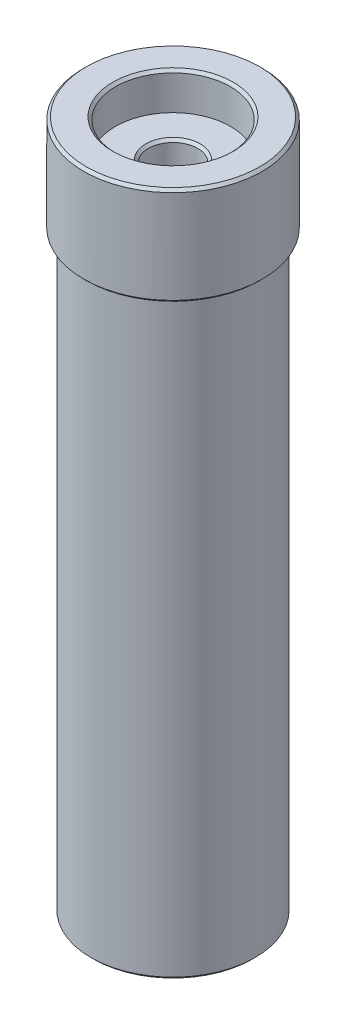
SolidWorks part; units mm, degrees
ref_plane "Front Plane" through (0, 0, 0) normal (0, 0, 1) x (1, 0, 0)
ref_plane "Top Plane" through (0, 0, 0) normal (0, 1, 0) x (1, 0, 0)
ref_plane "Right Plane" through (0, 0, 0) normal (1, 0, 0) x (0, 0, -1)
sketch "Sketch1" plane through (0, 0, 0) normal (0, 1, 0) x (1, 0, 0)
  circle A0 centre (0, 0) radius 15.875
  dimension "D1" = 31.75
extrude "Boss-Extrude1" add sketch "Sketch1" along normal blind 114.3
sketch "Sketch2" plane through (0, 114.3, 0) normal (0, 1, 0) x (1, 0, 0)
  circle A0 centre (0, 0) radius 17.272
  dimension "D1" = 34.544
extrude "Boss-Extrude2" add sketch "Sketch2" along normal blind 19.05
sketch "Sketch10" plane through (0, 133.35, 0) normal (0, 1, 0) x (1, 0, 0)
  circle A0 centre (0, 0) radius 11.1125
  dimension "D1" = 22.225
extrude "Cut-Extrude1" cut sketch "Sketch10" against normal blind 7.1628
hole_wizard "3/8 (0.375) Diameter Hole1" positions "Sketch11" profile "Sketch12" hole size "3/8" standard "ANSI Inch" end condition through all
sketch "Sketch11" plane through (0, 126.1872, 0) normal (0, 1, 0) x (1, 0, 0)
  point P1 (0, 0)
sketch "Sketch12" plane through (0, 126.1872, 0) normal (1, 0, 0) x (0, 0, 1)
  line L0 (0, 0) -> (0, 126.1872)
  line L1 (0, 126.1872) -> (4.7625, 126.1872)
  line L2 (4.7625, 126.1872) -> (4.7625, 0)
  line L5 (4.7625, 0) -> (0, 0)
  line L11 (0, -6.35) -> (0, 107.95) construction
  dimension "Thru Hole Dia." = 9.525
  dimension "Thru Hole Depth" = 126.1872
sketch "Sketch15" plane through (0, 0, 0) normal (0, -1, 0) x (1, 0, 0)
  circle A0 centre (0, 0) radius 11.7078
  dimension "D1" = 23.4156
extrude "Cut-Extrude3" cut sketch "Sketch15" against normal offset from surface (111.125 mm away) 3.175 up to face at (0, 114.3, 15.875)
sketch "Sketch16" plane through (0, 111.125, 0) normal (0, -1, 0) x (1, 0, 0)
  circle A0 centre (0, 0) radius 8.3344
  dimension "D1" = 16.6687
extrude "Cut-Extrude4" cut sketch "Sketch16" against normal blind 7.9375
chamfer "Chamfer2" distance 0.508 angle 45 5 edges at (0, 0, 15.875) (0, 114.3, 17.272) (0, 133.35, 17.272) (0, 126.1872, 4.7625) (0, 133.35, 11.1125)
